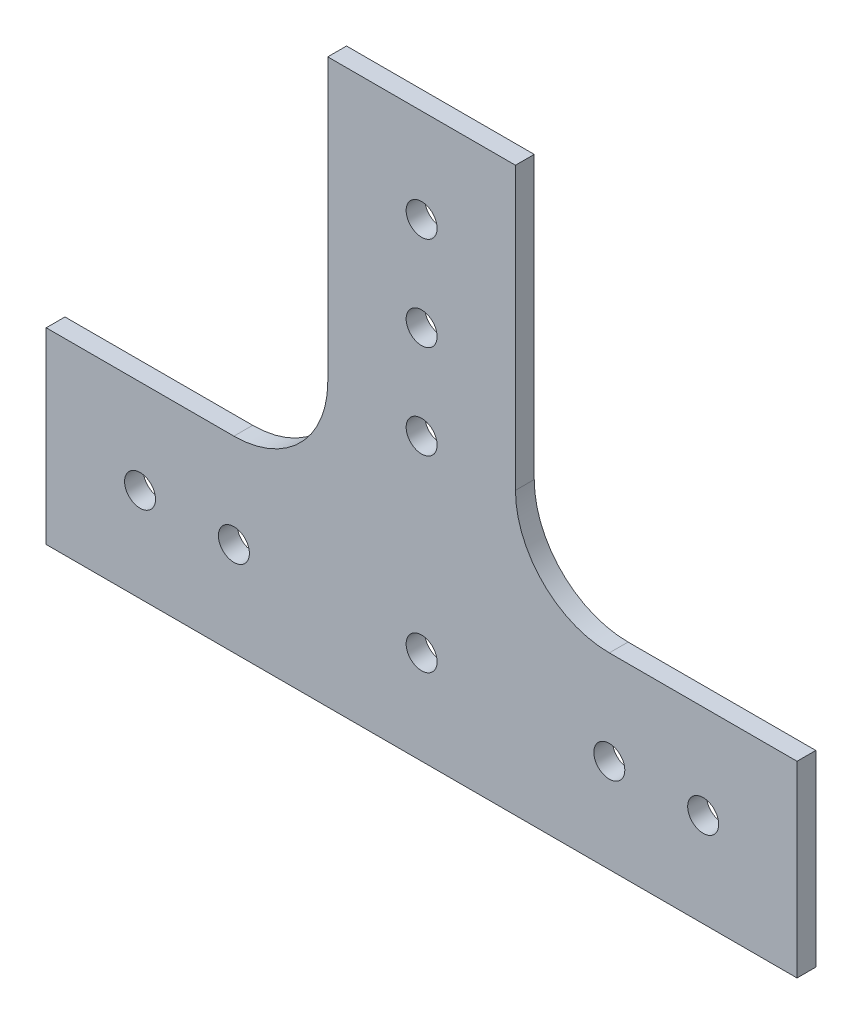
SolidWorks part; units mm, degrees
ref_plane "前视基准面" through (0, 0, 0) normal (0, 0, 1) x (1, 0, 0)
ref_plane "上视基准面" through (0, 0, 0) normal (0, 1, 0) x (1, 0, 0)
ref_plane "右视基准面" through (0, 0, 0) normal (1, 0, 0) x (0, 0, -1)
other "Configuration Table"
sketch "草图1" plane through (0, 0, 0) normal (0, 0, 1) x (1, 0, 0)
  line L0 (10, 10) -> (30, 10)
  line L1 (-30, -10) -> (30, -10)
  line L3 (-30, 10) -> (-10, 10)
  line L5 (-30, -10) -> (30, 10) construction
  line L6 (-30, 10) -> (30, -10) construction
  line L8 (-10, 10) -> (-10, 50)
  line L9 (-10, 50) -> (10, 50)
  line L10 (10, 10) -> (10, 50)
  line L11 (-30, 10) -> (-40, 10)
  line L12 (-40, 10) -> (-40, -10)
  line L13 (-40, -10) -> (-30, -10)
  line L14 (30, 10) -> (40, 10)
  line L15 (40, 10) -> (40, -10)
  line L16 (40, -10) -> (30, -10)
  circle A0 centre (0, 0) radius 1.65
  circle A1 centre (-20, 0) radius 1.65
  circle A2 centre (20, 0) radius 1.65
  circle A4 centre (0, 20) radius 1.65
  circle A5 centre (0, 30) radius 1.65
  circle A6 centre (0, 40) radius 1.65
  circle A7 centre (30, 0) radius 1.65
  circle A8 centre (-30, 0) radius 1.65
  point P0 (0, 0)
  dimension "D6" = 3.3
  dimension "D10" = 3.3
  dimension "D11" = 3.3
  dimension "D14" = 3.3
  dimension "D15" = 3.3
  dimension "D1" = 20
  dimension "D2" = 20
  dimension "D3" = 30
  dimension "D5" = 40
  dimension "D12" = 10
  dimension "D13" = 10
extrude "凸台-拉伸1" add sketch "草图1" along normal blind 2
fillet "圆角1" radius 10 2 edges at (10, 10, 1) (-10, 10, 1)
